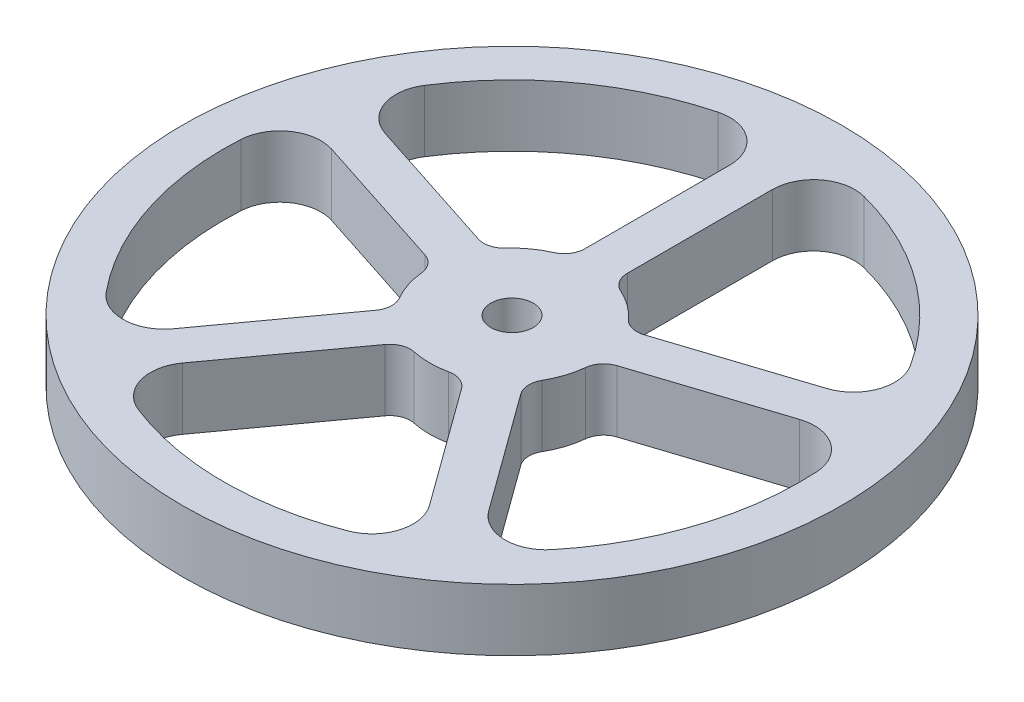
SolidWorks part; units mm, degrees
ref_plane "Front Plane" through (0, 0, 0) normal (0, 0, 1) x (1, 0, 0)
ref_plane "Top Plane" through (0, 0, 0) normal (0, 1, 0) x (1, 0, 0)
ref_plane "Right Plane" through (0, 0, 0) normal (1, 0, 0) x (0, 0, -1)
sketch "Sketch1" plane through (0, 0, 0) normal (0, 1, 0) x (1, 0, 0)
  line L0 (-2.575, 11.4234) -> (-2.575, 29.0279)
  line L1 (2.575, 11.4234) -> (2.575, 29.0279)
  line L2 (10.0686, 5.979) -> (26.8115, 11.4191)
  line L3 (11.66, 1.0811) -> (28.4029, 6.5211)
  line L4 (8.7977, -7.7282) -> (19.1454, -21.9705)
  line L5 (4.6313, -10.7553) -> (14.979, -24.9976)
  line L6 (-4.6313, -10.7553) -> (-14.979, -24.9976)
  line L7 (-8.7977, -7.7282) -> (-19.1454, -21.9705)
  line L8 (-11.66, 1.0811) -> (-28.4029, 6.5211)
  line L9 (-10.0686, 5.979) -> (-26.8115, 11.4191)
  arc A0 (-4.06, 9.1387) -> (-7.4368, 6.6853) centre (0, 0) ccw
  circle A1 centre (0, 0) radius 2.575
  circle A2 centre (0, 0) radius 40
  arc A3 (-8.8375, 33.8659) -> (-29.4774, 18.8701) centre (0, 0) ccw
  arc A4 (-34.9393, 2.0602) -> (-27.0556, -22.2035) centre (0, 0) ccw
  arc A5 (-9.9461, -1.0373) -> (-8.6562, -5.007) centre (0, 0) ccw
  arc A6 (-2.087, -9.7798) -> (2.087, -9.7798) centre (0, 0) ccw
  arc A7 (-12.7562, -32.5926) -> (12.7562, -32.5926) centre (0, 0) ccw
  arc A8 (27.0556, -22.2035) -> (34.9393, 2.0602) centre (0, 0) ccw
  arc A9 (8.6562, -5.007) -> (9.9461, -1.0373) centre (0, 0) ccw
  arc A10 (7.4368, 6.6853) -> (4.06, 9.1387) centre (0, 0) ccw
  arc A11 (29.4774, 18.8701) -> (8.8375, 33.8659) centre (0, 0) ccw
  arc A12 (-11.66, 1.0811) -> (-9.9461, -1.0373) centre (-12.4326, -1.2966) cw
  arc A13 (-8.7977, -7.7282) -> (-8.6562, -5.007) centre (-10.8203, -6.2587) ccw
  arc A14 (-4.6313, -10.7553) -> (-2.087, -9.7798) centre (-2.6088, -12.2247) cw
  arc A15 (4.6313, -10.7553) -> (2.087, -9.7798) centre (2.6088, -12.2247) ccw
  arc A16 (8.7977, -7.7282) -> (8.6562, -5.007) centre (10.8203, -6.2587) cw
  arc A17 (11.66, 1.0811) -> (9.9461, -1.0373) centre (12.4326, -1.2966) ccw
  arc A18 (10.0686, 5.979) -> (7.4368, 6.6853) centre (9.2961, 8.3566) cw
  arc A19 (2.575, 11.4234) -> (4.06, 9.1387) centre (5.075, 11.4234) ccw
  arc A20 (-2.575, 11.4234) -> (-4.06, 9.1387) centre (-5.075, 11.4234) cw
  arc A21 (-10.0686, 5.979) -> (-7.4368, 6.6853) centre (-9.2961, 8.3566) ccw
  arc A22 (28.4029, 6.5211) -> (34.9393, 2.0602) centre (29.948, 1.7659) cw
  arc A23 (26.8115, 11.4191) -> (29.4774, 18.8701) centre (25.2664, 16.1744) ccw
  arc A24 (2.575, 29.0279) -> (8.8375, 33.8659) centre (7.575, 29.0279) cw
  arc A25 (19.1454, -21.9705) -> (27.0556, -22.2035) centre (23.1905, -19.0316) ccw
  arc A26 (14.979, -24.9976) -> (12.7562, -32.5926) centre (10.9339, -27.9365) cw
  arc A27 (-14.979, -24.9976) -> (-12.7562, -32.5926) centre (-10.9339, -27.9365) ccw
  arc A28 (-19.1454, -21.9705) -> (-27.0556, -22.2035) centre (-23.1905, -19.0316) cw
  arc A29 (-2.575, 29.0279) -> (-8.8375, 33.8659) centre (-7.575, 29.0279) ccw
  arc A30 (-26.8115, 11.4191) -> (-29.4774, 18.8701) centre (-25.2664, 16.1744) cw
  arc A31 (-28.4029, 6.5211) -> (-34.9393, 2.0602) centre (-29.948, 1.7659) ccw
  point P26 (0, 0)
  dimension "D1" = 5.15
  dimension "D2" = 20
  dimension "D3" = 80
  dimension "D4" = 70
  dimension "D6" = 2.5
  dimension "D7" = 5
  dimension "D5" = 5
extrude "Boss-Extrude1" add sketch "Sketch1" along normal blind 7.5
